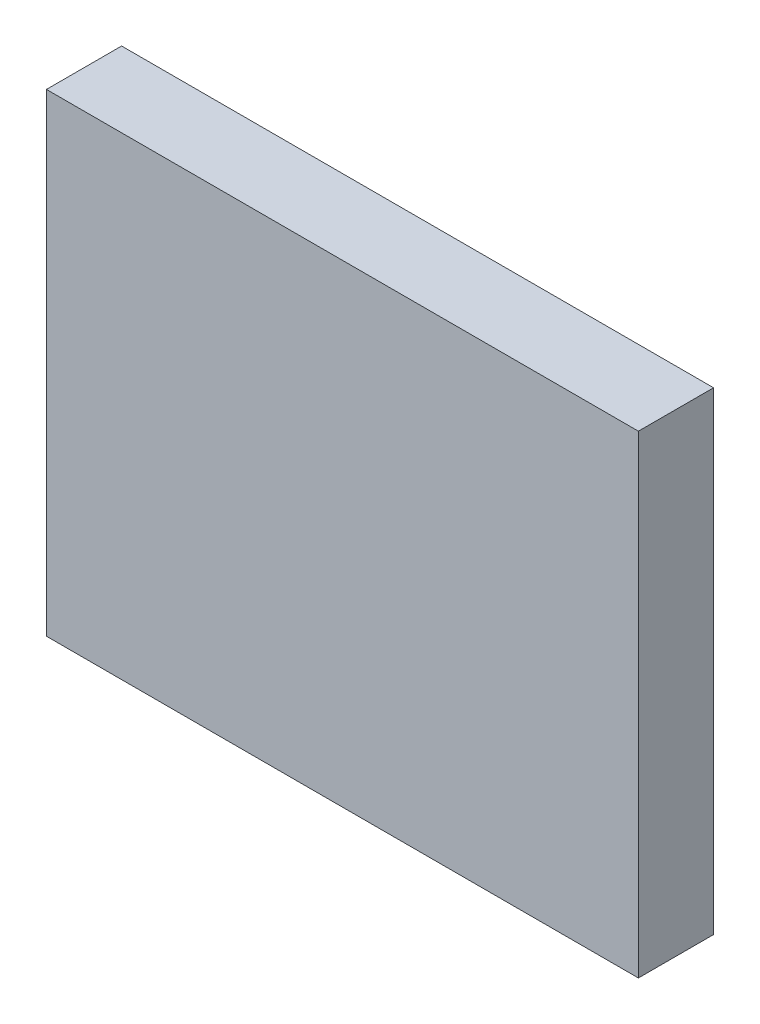
SolidWorks part; units mm, degrees
ref_plane "Front Plane" through (0, 0, 0) normal (0, 0, 1) x (1, 0, 0)
ref_plane "Top Plane" through (0, 0, 0) normal (0, 1, 0) x (1, 0, 0)
ref_plane "Right Plane" through (0, 0, 0) normal (1, 0, 0) x (0, 0, -1)
sketch "Sketch1" plane through (0, 0, 0) normal (0, 0, 1) x (1, 0, 0)
  line L1 (100, -80) -> (-100, -80)
  line L2 (100, -80) -> (100, 80)
  line L3 (100, 80) -> (-100, 80)
  line L4 (-100, -80) -> (-100, 80)
  line L5 (100, -80) -> (-100, 80) construction
  line L6 (100, 80) -> (-100, -80) construction
  point P0 (0, 0)
  dimension "D1" = 200
  dimension "D2" = 160
extrude "Boss-Extrude1" add sketch "Sketch1" along normal blind 25.4
